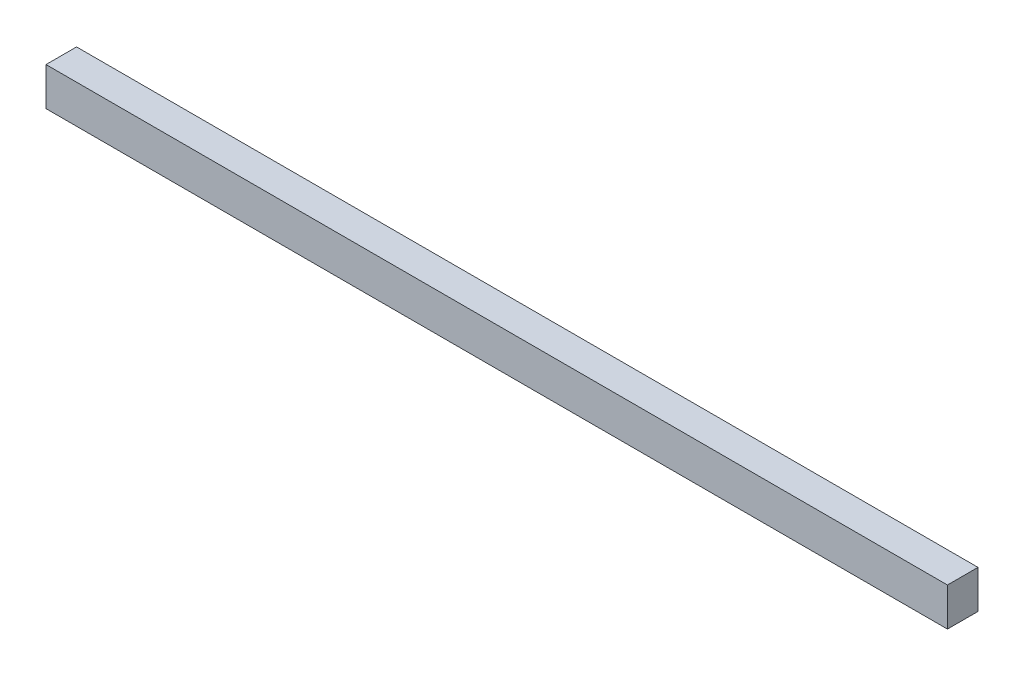
SolidWorks part; units mm, degrees
ref_plane "Front Plane" through (0, 0, 0) normal (0, 0, 1) x (1, 0, 0)
ref_plane "Top Plane" through (0, 0, 0) normal (0, 1, 0) x (1, 0, 0)
ref_plane "Right Plane" through (0, 0, 0) normal (1, 0, 0) x (0, 0, -1)
other "Configuration Table"
sketch "Sketch1" plane through (0, 0, 0) normal (0, 0, 1) x (1, 0, 0)
  line L1 (25, 0) -> (615, 0)
  line L2 (25, 0) -> (25, 25)
  line L3 (25, 25) -> (615, 25)
  line L4 (615, 0) -> (615, 25)
extrude "FKAP_cerceve_alt_1" add sketch "Sketch1" along normal blind 20 from offset 20 separate body
